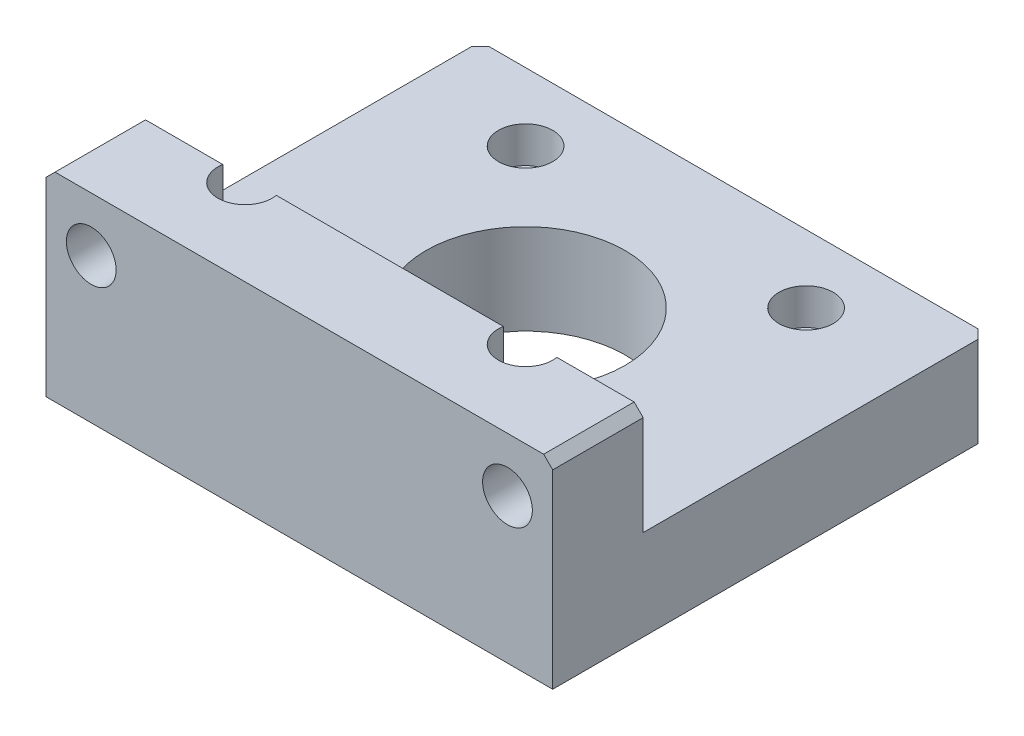
SolidWorks part; units mm, degrees
ref_plane "前视基准面" through (0, 0, 0) normal (0, 0, 1) x (1, 0, 0)
ref_plane "上视基准面" through (0, 0, 0) normal (0, 1, 0) x (1, 0, 0)
ref_plane "右视基准面" through (0, 0, 0) normal (1, 0, 0) x (0, 0, -1)
sketch "草图1" plane through (0, 0, 0) normal (0, 1, 0) x (1, 0, 0)
  line L1 (0, 0) -> (56, 0)
  line L2 (0, 0) -> (0, 48)
  line L3 (0, 48) -> (56, 48)
  line L4 (56, 0) -> (56, 48)
  dimension "D1" = 56
  dimension "D2" = 48
extrude "凸台-拉伸1" add sketch "草图1" along normal blind 10
sketch "草图2" plane through (0, 10, 0) normal (0, 1, 0) x (1, 0, 0)
  line L0 (28, 48) -> (28, 0) construction
  line L1 (56, 48) -> (0, 48) construction
  line L2 (0, 0) -> (56, 0) construction
  line L3 (0, 25) -> (56, 25) construction
  line L4 (0, 48) -> (0, 0) construction
  line L5 (56, 0) -> (56, 48) construction
  circle A0 centre (28, 25) radius 11
  dimension "D1" = 22
  dimension "D2" = 25
extrude "切除-拉伸1" cut sketch "草图2" against normal up to surface (10 mm away) up to face at (28, 0, -24)
hole_wizard "Ø3.5 (3.5) 直径孔1" positions "草图4" profile "草图3" hole size "Ø3.5" standard "GB"
sketch "草图4" plane through (0, 10, 0) normal (0, 1, 0) x (1, 0, 0)
  line L0 (28, 36) -> (28, 25) construction
  line L1 (28, 25) -> (39, 25) construction
  circle A0 centre (28, 25) radius 11 construction
  point P0 (12.5, 40.5)
  point P2 (43.5, 40.5)
  point P4 (43.5, 9.5)
  point P6 (12.5, 9.5)
  dimension "D1" = 31
  dimension "D2" = 31
sketch "草图3" plane through (12.5, 10, -40.5) normal (1, 0, 0) x (0, 0, 1)
  line L0 (0, 0) -> (0, 10)
  line L1 (0, 10) -> (1.75, 10)
  line L2 (1.75, 10) -> (1.75, 0)
  line L5 (1.75, 0) -> (0, 0)
  line L10 (0, 10) -> (-1.75, 10) construction
  line L11 (0, -6.35) -> (0, 107.95) construction
  dimension "孔直径" = 3.5
  dimension "孔深度" = 10
  dimension "导头角度" = 180
sketch "草图8" plane through (0, 10, 0) normal (0, 1, 0) x (1, 0, 0)
  line L0 (56, 0) -> (56, 48) construction
  line L1 (0, 0) -> (56, 0)
  line L2 (0, 0) -> (0, 10)
  line L3 (0, 10) -> (56, 10)
  line L4 (56, 0) -> (56, 10)
  dimension "D1" = 10
extrude "凸台-拉伸2" add sketch "草图8" along normal blind 12
hole_wizard "Ø5.5 (5.5) 直径孔1" positions "草图10" profile "草图9" hole size "Ø5.5" standard "GB"
sketch "草图10" plane through (0, 0, -10) normal (0, 0, -1) x (-1, 0, 0)
  line L0 (-28, 22) -> (-28, 0) construction
  line L1 (-56, 22) -> (0, 22) construction
  line L2 (-56, 0) -> (0, 0) construction
  point P0 (-51, 16)
  point P2 (-5, 16)
  dimension "D1" = 46
  dimension "D2" = 6
sketch "草图9" plane through (51, 16, -10) normal (1, 0, 0) x (0, 1, 0)
  line L0 (0, 0) -> (0, 10)
  line L1 (0, 10) -> (2.75, 10)
  line L2 (2.75, 10) -> (2.75, 0)
  line L5 (2.75, 0) -> (0, 0)
  line L10 (0, 10) -> (-2.75, 10) construction
  line L11 (0, -6.35) -> (0, 107.95) construction
  dimension "孔直径" = 5.5
  dimension "孔深度" = 10
  dimension "导头角度" = 180
sketch "草图11" plane through (0, 22, 0) normal (0, 1, 0) x (1, 0, 0)
  circle A0 centre (12.5, 9.5) radius 3
  circle A1 centre (43.5, 9.5) radius 3
  dimension "D1" = 6
extrude "切除-拉伸2" cut sketch "草图11" against normal blind 16
sketch "草图13" plane through (0, 10, 0) normal (0, 1, 0) x (1, 0, 0)
  circle A0 centre (12.5, 40.5) radius 3
  circle A1 centre (43.5, 40.5) radius 3
  dimension "D1" = 6
extrude "切除-拉伸3" cut sketch "草图13" against normal up to surface (4 mm away) up to face at (12.5, 6, -6.5)
hole_wizard "Ø5.0 (5) 直径孔1" positions "草图16" profile "草图15" hole size "Ø5.0" standard "GB"
sketch "草图16" plane through (0, 0, -10) normal (0, 0, -1) x (-1, 0, 0)
  line L0 (-51, 16) -> (-5, 16) construction
  point P0 (-28, 16)
sketch "草图15" plane through (28, 16, -10) normal (1, 0, 0) x (0, 1, 0)
  line L0 (0, 0) -> (0, 14)
  line L1 (0, 14) -> (2.5, 14)
  line L2 (2.5, 14) -> (2.5, 0)
  line L5 (2.5, 0) -> (0, 0)
  line L10 (0, 14) -> (-2.5, 14) construction
  line L11 (0, -6.35) -> (0, 107.95) construction
  dimension "孔直径" = 5
  dimension "孔深度" = 14
  dimension "导头角度" = 180
chamfer "倒角1" distance 1 angle 45 2 edges at (56, 5, -48) (0, 5, -48)
chamfer "倒角2" distance 1 angle 45 2 edges at (56, 22, -5) (0, 22, -5)
